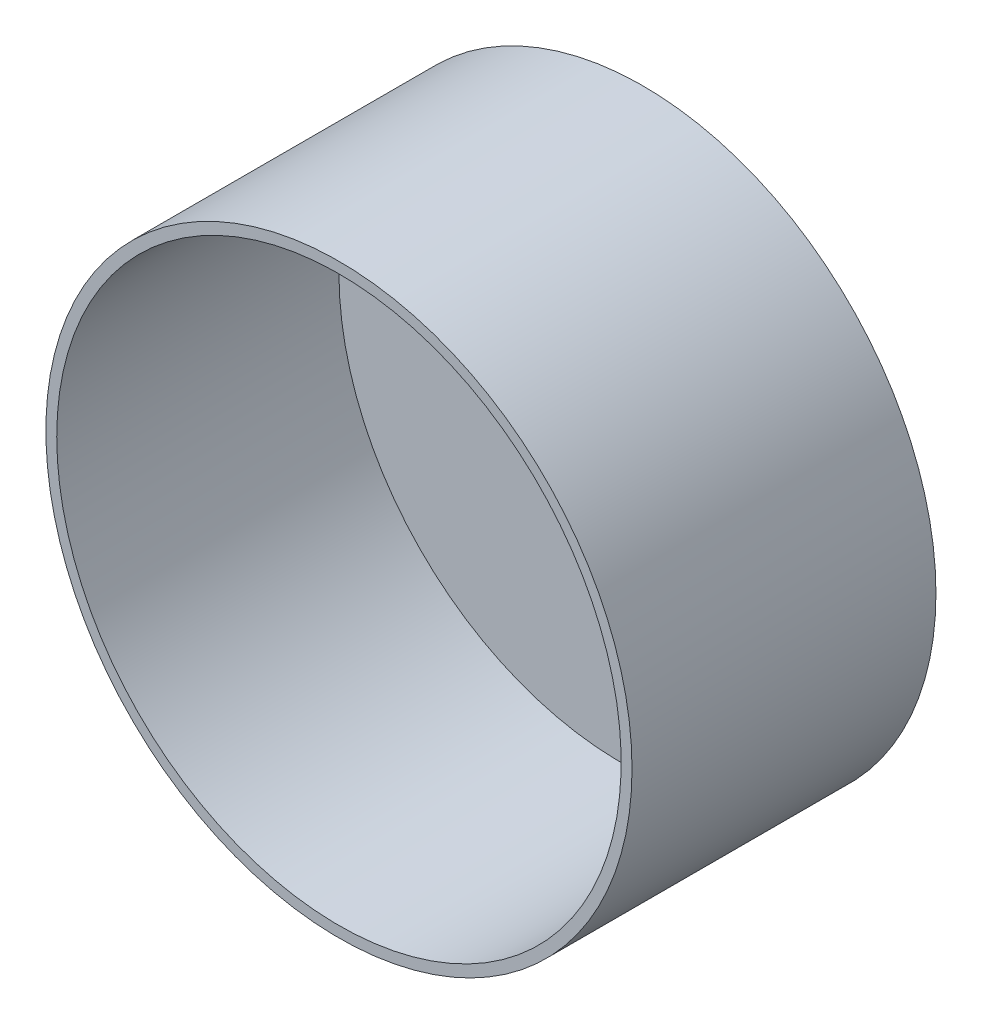
SolidWorks part; units mm, degrees
ref_plane "Front Plane" through (0, 0, 0) normal (0, 0, 1) x (1, 0, 0)
ref_plane "Top Plane" through (0, 0, 0) normal (0, 1, 0) x (1, 0, 0)
ref_plane "Right Plane" through (0, 0, 0) normal (1, 0, 0) x (0, 0, -1)
sketch "Sketch1" plane through (0, 0, 0) normal (0, 0, 1) x (1, 0, 0)
  circle A0 centre (0, 0) radius 13.5
  dimension "D1" = 27
extrude "Boss-Extrude1" add sketch "Sketch1" along normal blind 1
sketch "Sketch2" plane through (0, 0, 1) normal (0, 0, 1) x (1, 0, 0)
  circle A0 centre (0, 0) radius 13.5
  circle A1 centre (0, 0) radius 13
  circle A2 centre (0, 0) radius 13.5 construction
  dimension "D1" = 0.5
extrude "Boss-Extrude2" add sketch "Sketch2" along normal blind 13
